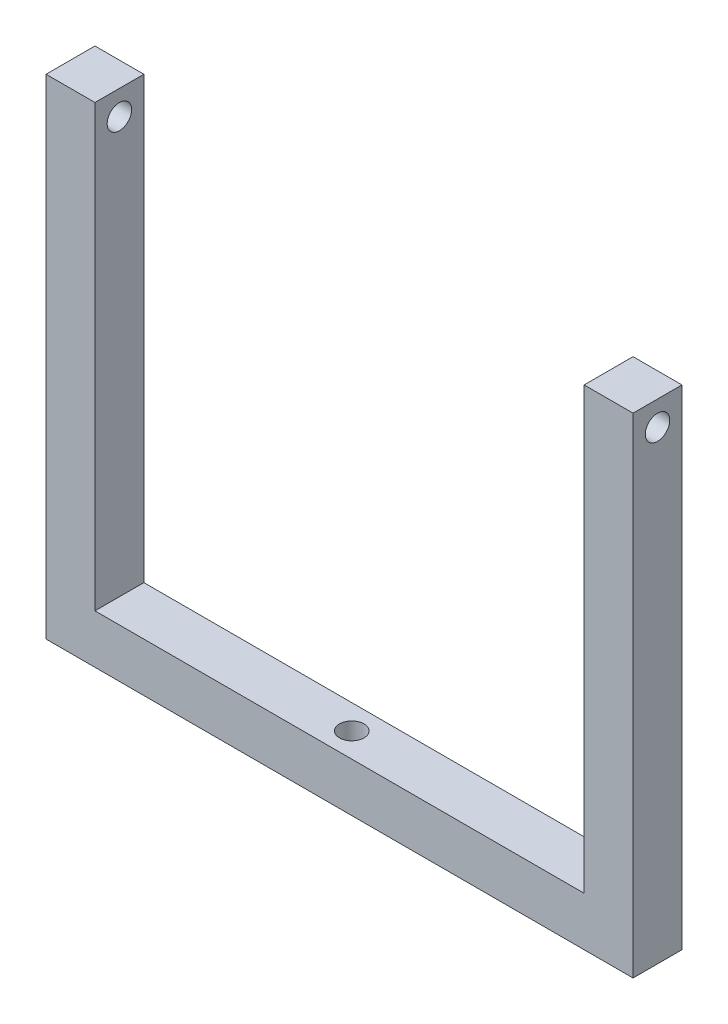
SolidWorks part; units mm, degrees
ref_plane "Front Plane" through (0, 0, 0) normal (0, 0, 1) x (1, 0, 0)
ref_plane "Top Plane" through (0, 0, 0) normal (0, 1, 0) x (1, 0, 0)
ref_plane "Right Plane" through (0, 0, 0) normal (1, 0, 0) x (0, 0, -1)
sketch "Sketch1" plane through (0, 0, 0) normal (0, 0, 1) x (1, 0, 0)
  line L0 (0, 0) -> (-12.7, 0)
  line L1 (-12.7, 0) -> (-12.7, -127)
  line L2 (-12.7, -127) -> (139.7, -127)
  line L3 (139.7, -127) -> (139.7, 0)
  line L4 (139.7, 0) -> (127, 0)
  line L5 (127, 0) -> (127, -114.3)
  line L6 (127, -114.3) -> (0, -114.3)
  line L7 (0, -114.3) -> (0, 0)
  dimension "D1" = 127
  dimension "D2" = 152.4
  dimension "D3" = 12.7
  dimension "D4" = 12.7
  dimension "D5" = 12.7
extrude "Boss-Extrude1" add sketch "Sketch1" along normal blind 12.7 contours L1 L2 L3 L4 L5 L6 L7 L0
sketch "Sketch2" plane through (-12.7, 0, 0) normal (-1, 0, 0) x (0, 0, 1)
  line L0 (0, 0) -> (0, -127) construction
  line L1 (12.7, 0) -> (0, 0) construction
  circle A0 centre (6.35, -6.35) radius 3.175
  dimension "D1" = 6.35
  dimension "D2" = 6.35
extrude "Cut-Extrude1" cut sketch "Sketch2" against normal up to surface (152.4 mm away) up to face at (139.7, -63.5, 6.35)
sketch "Sketch3" plane through (0, -114.3, 0) normal (0, 1, 0) x (1, 0, 0)
  line L0 (127, 0) -> (0, 0) construction
  line L1 (0, -12.7) -> (0, 0) construction
  circle A0 centre (60.325, -6.35) radius 3.175
  dimension "D1" = 6.35
  dimension "D3" = 6.35
  dimension "D2" = 60.325
extrude "Cut-Extrude2" cut sketch "Sketch3" against normal up to surface (12.7 mm away) contours A0 up to face at (63.5, -127, 6.35)
